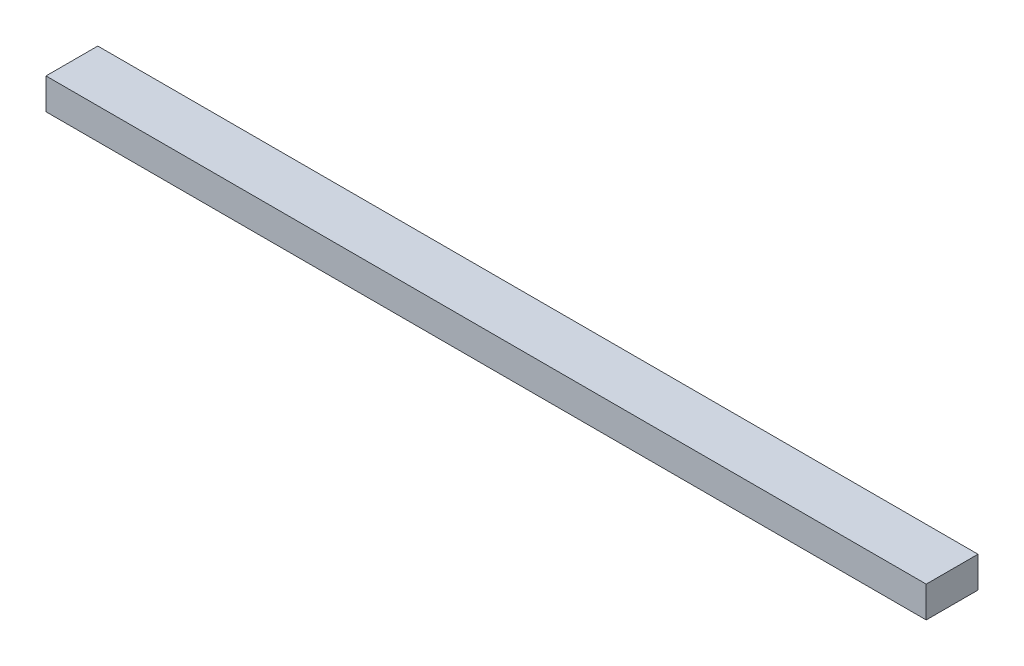
SolidWorks part; units mm, degrees
ref_plane "Front Plane" through (0, 0, 0) normal (0, 0, 1) x (1, 0, 0)
ref_plane "Top Plane" through (0, 0, 0) normal (0, 1, 0) x (1, 0, 0)
ref_plane "Right Plane" through (0, 0, 0) normal (1, 0, 0) x (0, 0, -1)
sketch "Sketch1" plane through (0, 0, 0) normal (0, 1, 0) x (1, 0, 0)
  line L1 (-85, 5) -> (85, 5)
  line L2 (-85, 5) -> (-85, -5)
  line L3 (-85, -5) -> (85, -5)
  line L4 (85, 5) -> (85, -5)
  line L5 (-85, 5) -> (85, -5) construction
  line L6 (-85, -5) -> (85, 5) construction
  point P0 (0, 0)
  dimension "D1" = 170
  dimension "D2" = 10
extrude "Boss-Extrude1" add sketch "Sketch1" along normal blind 6
